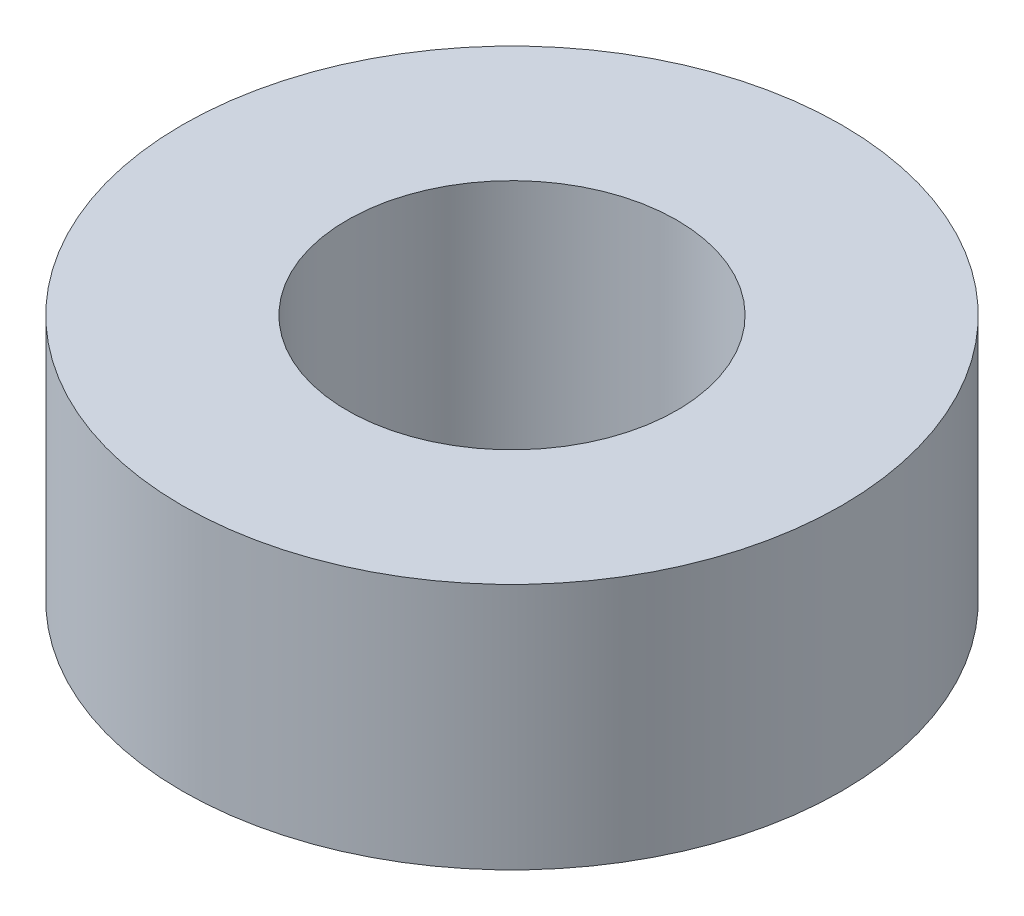
SolidWorks part; units mm, degrees
material "1023 Carbon Steel Sheet (SS)"
ref_plane "Front Plane" through (0, 0, 0) normal (0, 0, 1) x (1, 0, 0)
ref_plane "Top Plane" through (0, 0, 0) normal (0, 1, 0) x (1, 0, 0)
ref_plane "Right Plane" through (0, 0, 0) normal (1, 0, 0) x (0, 0, -1)
sketch "Sketch1" plane through (0, 0, 0) normal (0, 0, 1) x (1, 0, 0)
  line L0 (0, 0) -> (0, 1.9266) construction
  line L1 (-4, -1.5) -> (-2, -1.5)
  line L2 (-4, -1.5) -> (-4, 1.5)
  line L3 (-4, 1.5) -> (-2, 1.5)
  line L4 (-2, -1.5) -> (-2, 1.5)
  line L5 (-4, -1.5) -> (-2, 1.5) construction
  line L6 (-4, 1.5) -> (-2, -1.5) construction
  point P0 (-3, 0)
  dimension "D1" = 4
  dimension "D2" = 8
  dimension "D3" = 3
revolve "Revolve1" add sketch "Sketch1" angle 360 about L0
